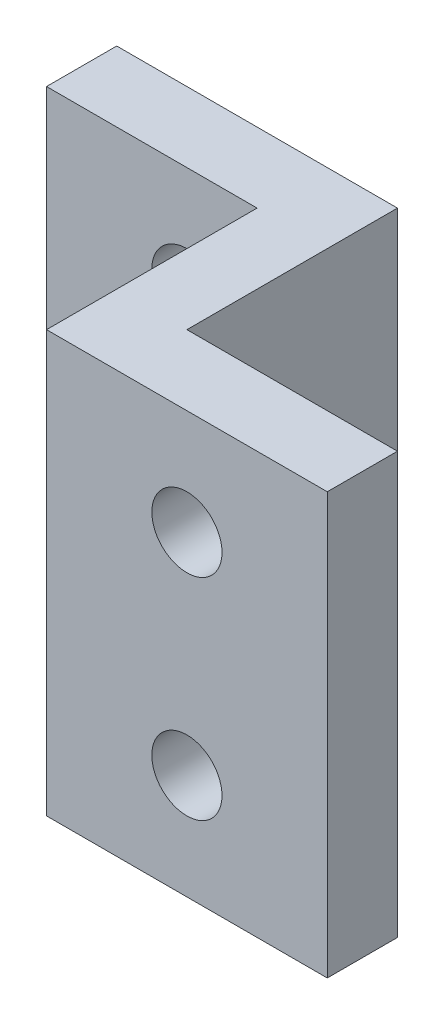
SolidWorks part; units mm, degrees
ref_plane "Ön Düzlem" through (0, 0, 0) normal (0, 0, 1) x (1, 0, 0)
ref_plane "Üst Düzlem" through (0, 0, 0) normal (0, 1, 0) x (1, 0, 0)
ref_plane "Sağ Düzlem" through (0, 0, 0) normal (1, 0, 0) x (0, 0, -1)
sketch "Çizim1" plane through (0, 0, 0) normal (0, 0, 1) x (1, 0, 0)
  line L0 (-21.1928, 21.7252) -> (-36.1928, 21.7252)
  line L1 (-36.1928, 21.7252) -> (-36.1928, -8.2748)
  line L2 (-36.1928, -8.2748) -> (-21.1928, -8.2748)
  line L3 (-21.1928, -8.2748) -> (-21.1928, 21.7252)
  line L4 (-31.1928, 23.679) -> (-31.1928, -16.3423) construction
  circle A0 centre (-31.1928, 14.2252) radius 2.5
  circle A1 centre (-31.1928, -0.7748) radius 2.5
  dimension "D3" = 5
  dimension "D4" = 5
  dimension "D1" = 15
  dimension "D2" = 30
  dimension "D5" = 5
  dimension "D6" = 7.5
  dimension "D7" = 7.5
extrude "Yükseklik-Ekstrüzyon1" add sketch "Çizim1" along normal blind 5
sketch "Çizim2" plane through (0, 0, 0) normal (0, 0, -1) x (-1, 0, 0)
  line L1 (36.1928, 21.7252) -> (41.1928, 21.7252)
  line L2 (36.1928, 21.7252) -> (36.1928, -8.2748)
  line L3 (36.1928, -8.2748) -> (41.1928, -8.2748)
  line L4 (41.1928, 21.7252) -> (41.1928, -8.2748)
  dimension "D1" = 30
  dimension "D2" = 5
extrude "Yükseklik-Ekstrüzyon2" add sketch "Çizim2" along normal blind 15 and the other way blind 5
sketch "Çizim3" plane through (0, 0, -15) normal (0, 0, -1) x (-1, 0, 0)
  line L1 (41.1928, -8.2748) -> (56.1928, -8.2748)
  line L2 (41.1928, -8.2748) -> (41.1928, 21.7252)
  line L3 (41.1928, 21.7252) -> (56.1928, 21.7252)
  line L4 (56.1928, -8.2748) -> (56.1928, 21.7252)
  dimension "D1" = 30
  dimension "D2" = 15
extrude "Yükseklik-Ekstrüzyon3" add sketch "Çizim3" against normal blind 5
sketch "Çizim4" plane through (0, 0, -10) normal (0, 0, 1) x (1, 0, 0)
  line L0 (-46.1928, 22.7044) -> (-46.1928, -9.9676) construction
  line L1 (-41.1928, -8.2748) -> (-56.1928, -8.2748) construction
  line L2 (-56.1928, -8.2748) -> (-56.1928, 21.7252) construction
  circle A0 centre (-46.1928, 14.2252) radius 2.5
  circle A1 centre (-46.1928, -0.7748) radius 2.5
  dimension "D1" = 5
  dimension "D2" = 5
  dimension "D3" = 15
  dimension "D4" = 7.5
  dimension "D5" = 10
extrude "Kes-Ekstrüzyon1" cut sketch "Çizim4" against normal blind 10
